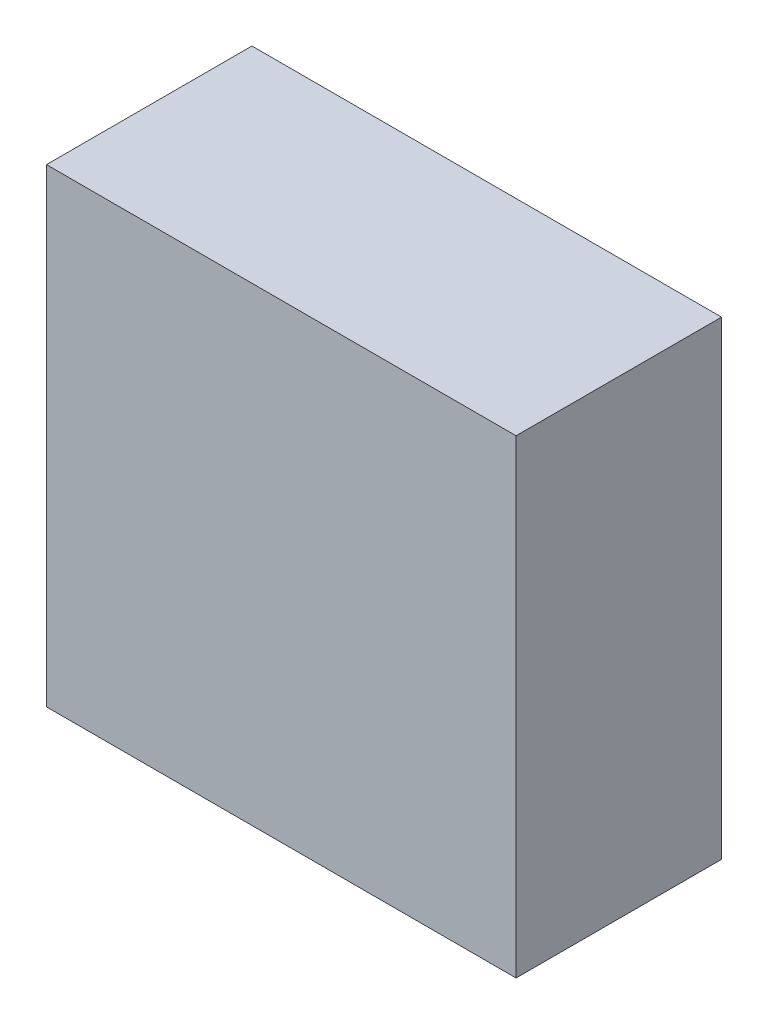
SolidWorks part; units mm, degrees
ref_plane "Front Plane" through (0, 0, 0) normal (0, 0, 1) x (1, 0, 0)
ref_plane "Top Plane" through (0, 0, 0) normal (0, 1, 0) x (1, 0, 0)
ref_plane "Right Plane" through (0, 0, 0) normal (1, 0, 0) x (0, 0, -1)
sketch "Sketch1" plane through (0, 0, 0) normal (0, 0, 1) x (1, 0, 0)
  line L1 (40, 40) -> (-40, 40)
  line L2 (40, 40) -> (40, -40)
  line L3 (40, -40) -> (-40, -40)
  line L4 (-40, 40) -> (-40, -40)
  line L5 (40, 40) -> (-40, -40) construction
  line L6 (40, -40) -> (-40, 40) construction
  point P0 (0, 0)
  dimension "D1" = 80
extrude "Boss-Extrude1" add sketch "Sketch1" along normal blind 35
